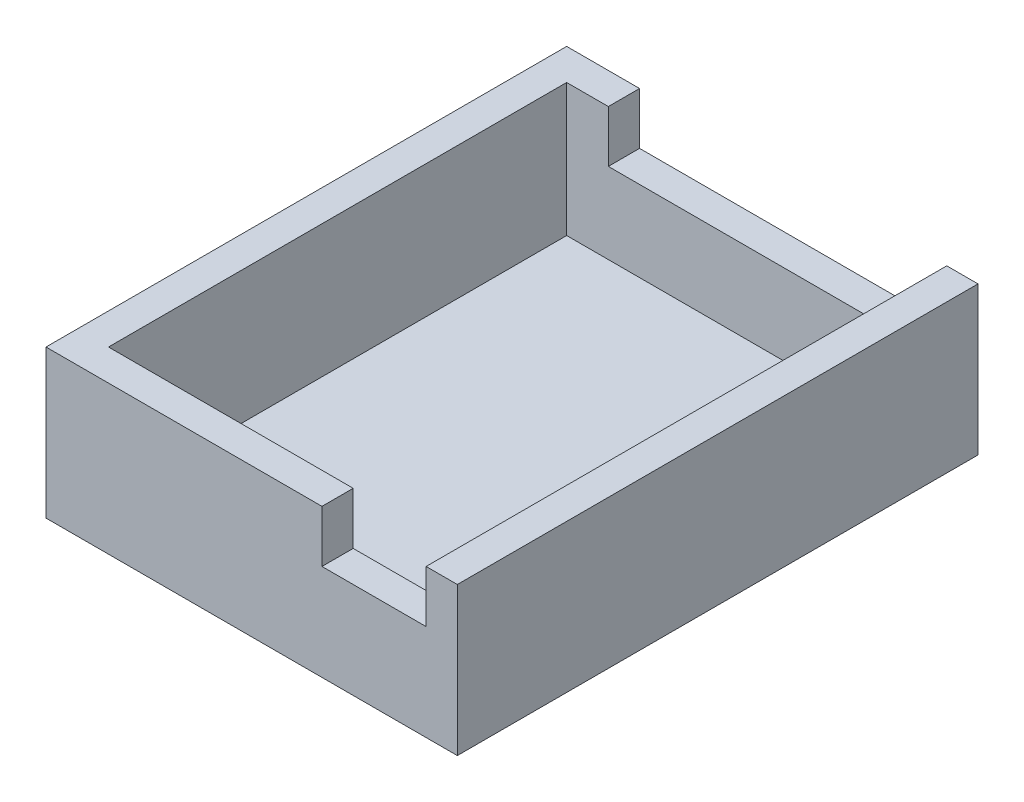
SolidWorks part; units mm, degrees
ref_plane "Front Plane" through (0, 0, 0) normal (0, 0, 1) x (1, 0, 0)
ref_plane "Top Plane" through (0, 0, 0) normal (0, 1, 0) x (1, 0, 0)
ref_plane "Right Plane" through (0, 0, 0) normal (1, 0, 0) x (0, 0, -1)
sketch "Sketch1" plane through (0, 0, 0) normal (0, 1, 0) x (1, 0, 0)
  line L1 (0, 0) -> (39.5, 0)
  line L2 (0, 0) -> (0, 50)
  line L3 (0, 50) -> (39.5, 50)
  line L4 (39.5, 0) -> (39.5, 50)
  dimension "D1" = 39.5
  dimension "D2" = 50
extrude "Boss-Extrude1" add sketch "Sketch1" along normal blind 1.5
sketch "Sketch3" plane through (0, 1.5, 0) normal (0, 1, 0) x (1, 0, 0)
  line L1 (0, 0) -> (39.5, 0)
  line L2 (0, 0) -> (0, 50)
  line L3 (0, 50) -> (39.5, 50)
  line L4 (39.5, 0) -> (39.5, 50)
  line L5 (3, 3) -> (36.5, 3)
  line L6 (3, 3) -> (3, 47)
  line L7 (3, 47) -> (36.5, 47)
  line L8 (36.5, 3) -> (36.5, 47)
  dimension "D1" = 44
  dimension "D2" = 33.5
  dimension "D3" = 3
  dimension "D4" = 3
extrude "Boss-Extrude2" add sketch "Sketch3" along normal blind 12.73
sketch "Sketch6" plane through (0, 0, 0) normal (0, 0, 1) x (1, 0, 0)
  line L0 (39.5, 14.23) -> (39.5, 0) construction
  line L1 (26.5, 14.23) -> (36.5, 14.23)
  line L2 (26.5, 14.23) -> (26.5, 9.23)
  line L3 (26.5, 9.23) -> (36.5, 9.23)
  line L4 (36.5, 14.23) -> (36.5, 9.23)
  line L5 (0, 0) -> (39.5, 0) construction
  point P4 (39.5, 7.115)
  dimension "D1" = 10
  dimension "D2" = 5
  dimension "D3" = 3
  dimension "D4" = 9.23
extrude "Cut-Extrude2" cut sketch "Sketch6" against normal blind 11.2
sketch "Sketch7" plane through (0, 0, -50) normal (0, 0, -1) x (-1, 0, 0)
  line L0 (-39.5, 14.23) -> (-39.5, 0) construction
  line L1 (-36.5, 14.23) -> (-7, 14.23)
  line L2 (-36.5, 14.23) -> (-36.5, 9.25)
  line L3 (-36.5, 9.25) -> (-7, 9.25)
  line L4 (-7, 14.23) -> (-7, 9.25)
  line L5 (-39.5, 0) -> (0, 0) construction
  dimension "D1" = 29.5
  dimension "D2" = 4.98
  dimension "D3" = 3
  dimension "D4" = 9.25
extrude "Cut-Extrude3" cut sketch "Sketch7" against normal blind 3.3
